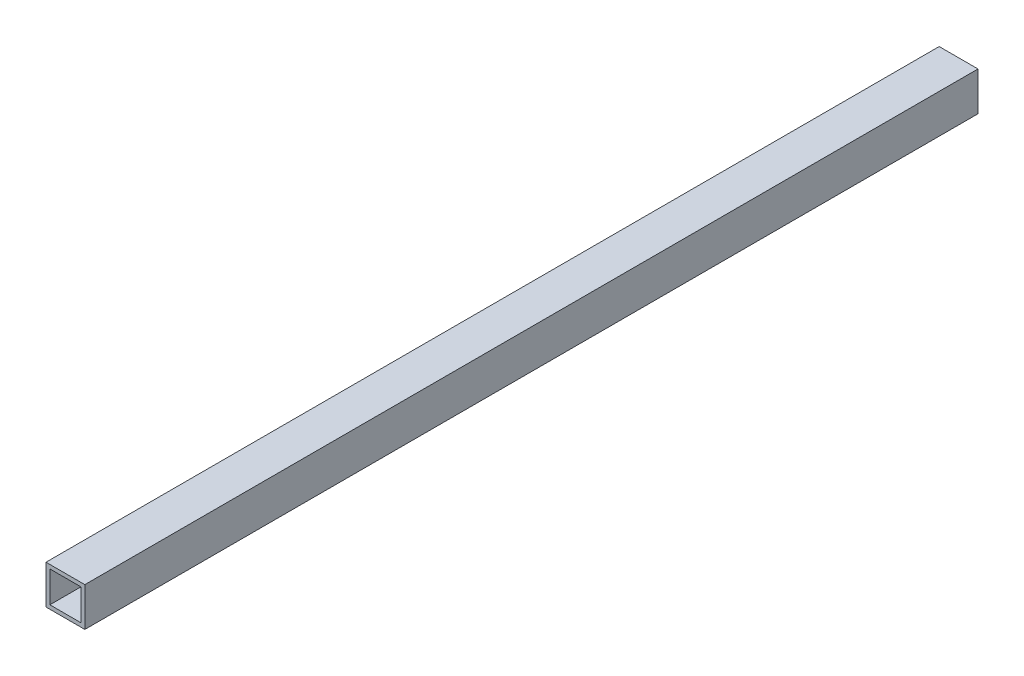
SolidWorks part; units mm, degrees
material "AISI 304"
ref_plane "Front Plane" through (0, 0, 0) normal (0, 0, 1) x (1, 0, 0)
ref_plane "Top Plane" through (0, 0, 0) normal (0, 1, 0) x (1, 0, 0)
ref_plane "Right Plane" through (0, 0, 0) normal (1, 0, 0) x (0, 0, -1)
sketch "Brace_Tube_Profile" plane through (0, 0, 0) normal (0, 0, 1) x (1, 0, 0)
  line L1 (-10, -10) -> (10, -10)
  line L2 (-10, -10) -> (-10, 10)
  line L3 (-10, 10) -> (10, 10)
  line L4 (10, -10) -> (10, 10)
  line L5 (-10, -10) -> (10, 10) construction
  line L6 (-10, 10) -> (10, -10) construction
  line L7 (-8, -8) -> (8, -8)
  line L8 (-8, -8) -> (-8, 8)
  line L9 (-8, 8) -> (8, 8)
  line L10 (8, -8) -> (8, 8)
  line L11 (-8, -8) -> (8, 8) construction
  line L12 (-8, 8) -> (8, -8) construction
  point P0 (0, 0)
  dimension "Half_Tube_Inner" = 8
  dimension "Half_Tube_Size" = 10
extrude "Brace_Length_460" add sketch "Brace_Tube_Profile" along normal mid plane 460
